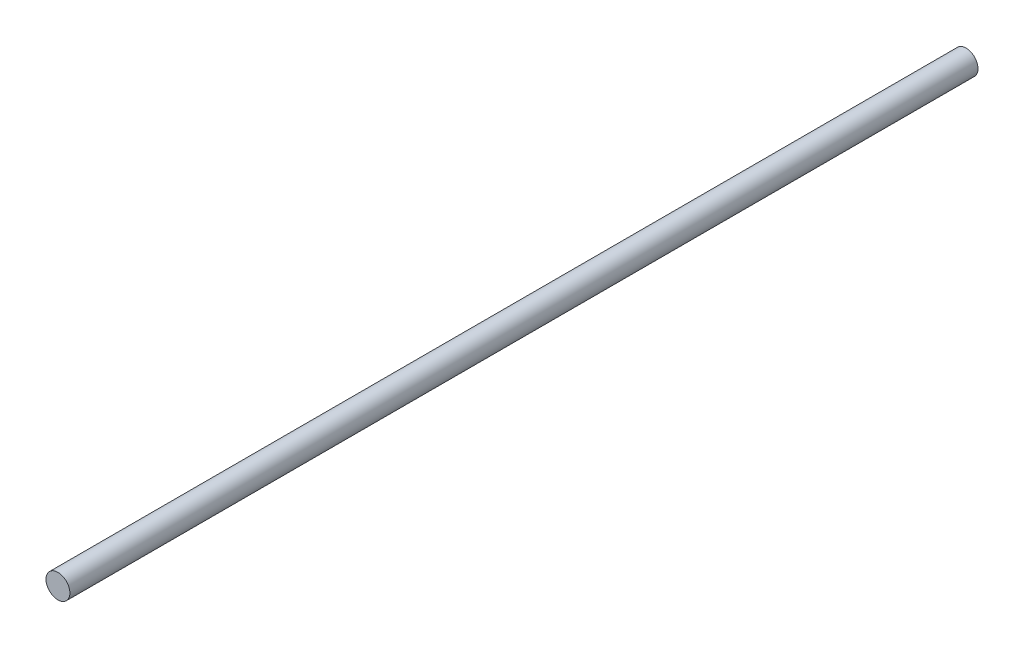
SolidWorks part; units mm, degrees
ref_plane "Front Plane" through (0, 0, 0) normal (0, 0, 1) x (1, 0, 0)
ref_plane "Top Plane" through (0, 0, 0) normal (0, 1, 0) x (1, 0, 0)
ref_plane "Right Plane" through (0, 0, 0) normal (1, 0, 0) x (0, 0, -1)
sketch "Sketch1" plane through (0, 0, 0) normal (0, 0, 1) x (1, 0, 0)
  circle A0 centre (0, 0) radius 2.5
  dimension "D1" = 5
extrude "Boss-Extrude1" add sketch "Sketch1" along normal blind 190 contours A0
